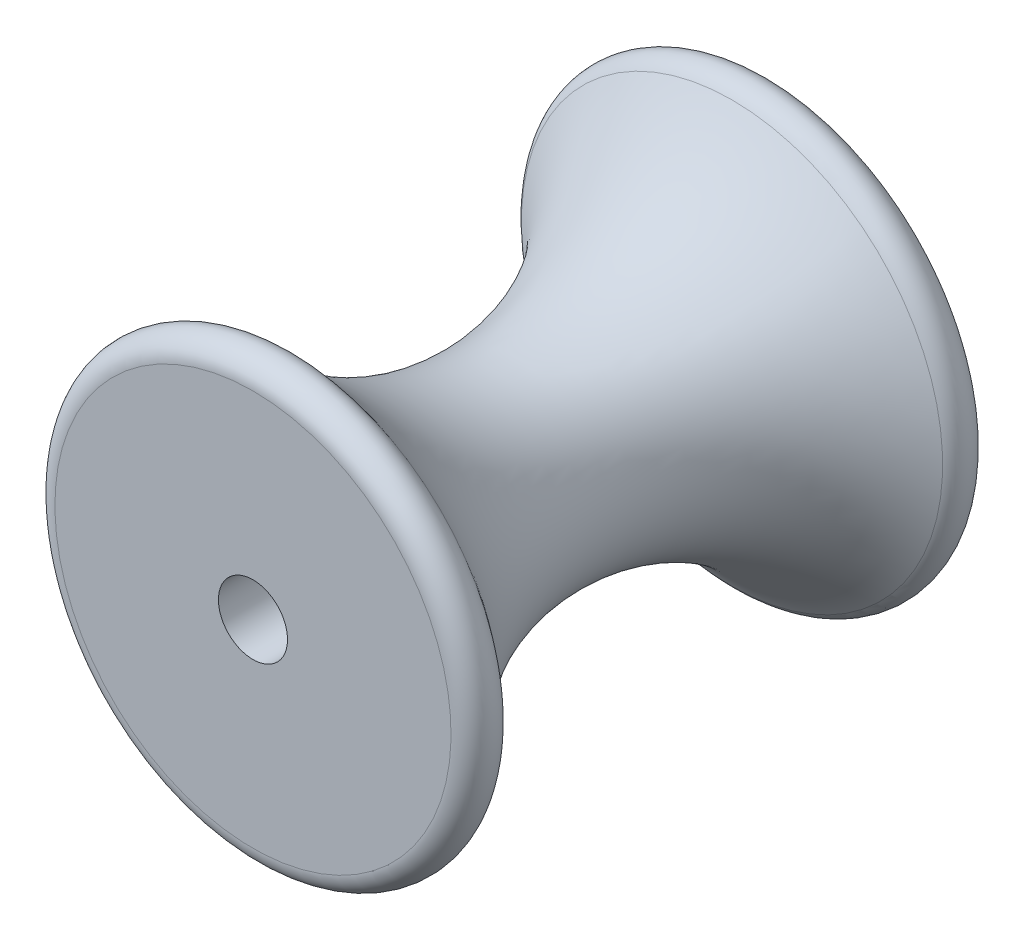
SolidWorks part; units mm, degrees
ref_plane "Front Plane" through (0, 0, 0) normal (0, 0, 1) x (1, 0, 0)
ref_plane "Top Plane" through (0, 0, 0) normal (0, 1, 0) x (1, 0, 0)
ref_plane "Right Plane" through (0, 0, 0) normal (1, 0, 0) x (0, 0, -1)
sketch "Sketch1" plane through (0, 0, 0) normal (1, 0, 0) x (0, 0, -1)
  line L0 (12.5, 0) -> (-12.5, 0) construction
  line L2 (12.5, 1.6) -> (-12.5, 1.6) construction
  line L3 (12.5, -24.0325) -> (12.5, -26.0603) construction
  line L4 (0, 11.1911) -> (0, -11.1911) construction
  line L5 (12.5, 1.6) -> (12.5, 17) construction
  line L6 (-12.5, 1.6) -> (-12.5, 17) construction
  line L7 (12, 1.6) -> (12, 13.5)
  line L8 (-12, 1.6) -> (-12, 13.5)
  line L9 (12, 1.6) -> (-12, 1.6)
  circle A0 centre (0, 17) radius 12.5 construction
  arc A1 (12, 13.5) -> (-12, 13.5) centre (0, 17) cw
  point P2 (0, 0)
  dimension "D1" = 1
revolve "Revolve1" add sketch "Sketch1" angle 360 about L0
fillet "Fillet1" radius 1 2 edges at (0, 13.5, 12) (0, 13.5, -12)
